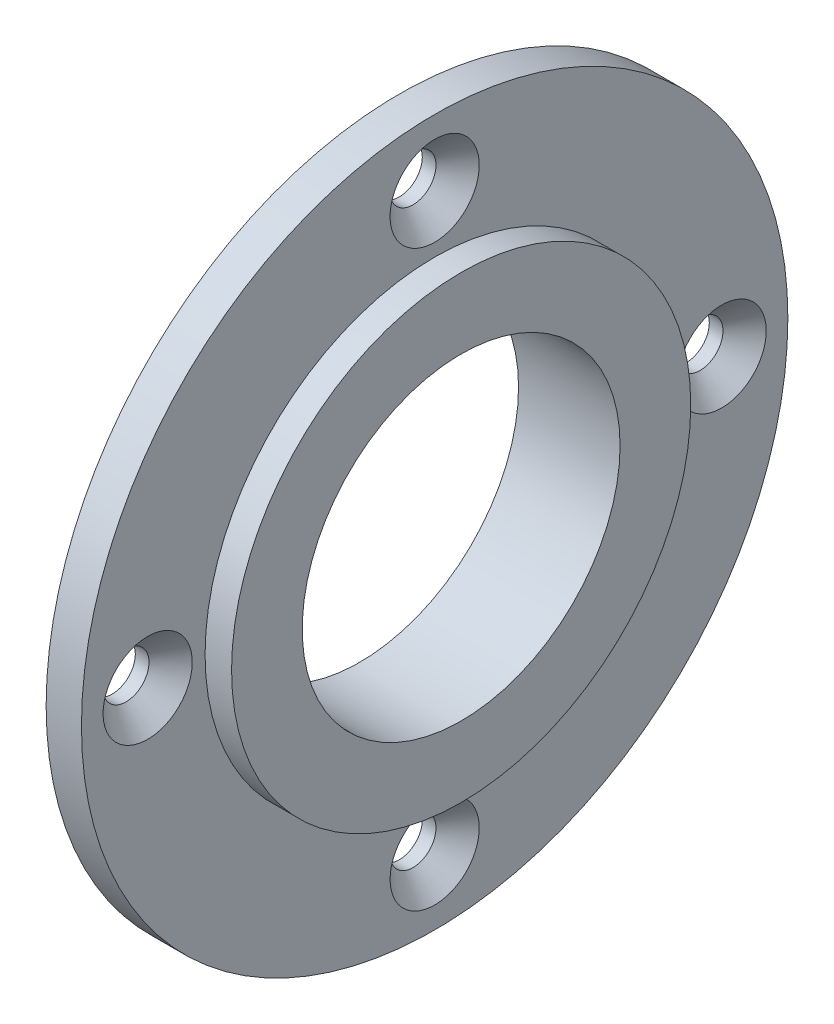
SolidWorks part; units mm, degrees
ref_plane "Front Plane" through (0, 0, 0) normal (0, 0, 1) x (1, 0, 0)
ref_plane "Top Plane" through (0, 0, 0) normal (0, 1, 0) x (1, 0, 0)
ref_plane "Right Plane" through (0, 0, 0) normal (1, 0, 0) x (0, 0, -1)
sketch "Sketch2" plane through (0, 0, 0) normal (0, 0, 1) x (1, 0, 0)
  line L0 (-174.9056, 26) -> (-177.9056, 26)
  line L1 (-177.9056, 26) -> (-177.9056, 40)
  line L2 (-177.9056, 40) -> (-181.9056, 40)
  line L3 (-181.9056, 40) -> (-181.9056, 21)
  line L4 (-186.4056, 18) -> (-174.9056, 18)
  line L5 (-174.9056, 18) -> (-174.9056, 26)
  line L6 (0, 0) -> (-61.0884, 0) construction
  line L7 (-182.4056, 18.3985) -> (-182.4056, 31.2775) construction
  line L8 (-181.9056, 21) -> (-186.4056, 21)
  line L9 (-186.4056, 21) -> (-186.4056, 18)
  line L14 (-198.4056, -21) -> (-198.4056, 21) construction
  dimension "D1" = 4
  dimension "D2" = 42
  dimension "D3" = 36
  dimension "D5" = 3
  dimension "D6" = 80
  dimension "D8" = 12
  dimension "D4" = 0.5
  dimension "D7" = 52
revolve "Revolve1" add sketch "Sketch2" angle 360 about L6
sketch "Sketch3" plane through (-177.9056, 0, 0) normal (1, 0, 0) x (0, 0, -1)
  circle A0 centre (0, 0) radius 32.5 construction
  circle A1 centre (0, 32.5) radius 3.3774
  dimension "D1" = 65
hole_wizard "CSK for M5 Countersunk Flat Head Screw1" positions "Sketch4" profile "Sketch5" countersink size "M5" standard "ISO" end condition through all
sketch "Sketch4" plane through (-177.9056, 0, 0) normal (1, 0, 0) x (0, 0, -1)
  point P0 (0, 32.5)
sketch "Sketch5" plane through (-177.9056, 32.5, 0) normal (0, 1, 0) x (0, 0, -1)
  line L0 (0, 0) -> (0, 8.5)
  line L1 (0, 8.5) -> (2.6, 8.5)
  line L2 (2.6, 8.5) -> (2.6, 2.45)
  line L3 (2.6, 2.45) -> (5.05, 0)
  line L5 (5.05, 0) -> (0, 0)
  line L6 (-2.6, 2.45) -> (-5.05, 0) construction
  line L11 (0, -6.35) -> (0, 107.95) construction
  dimension "Thru Hole Dia." = 5.2
  dimension "Thru Hole Depth" = 8.5
  dimension "Near C'Sink Dia." = 10.1
  dimension "Near C'Sink Angle" = 90
pattern_circular "CirPattern1" count 4 over 360 about axis through (0, 0, 0) along (1, 0, 0) of "CSK for M5 Countersunk Flat Head Screw1"
equation "\"l-x_vis_flasque_rouleau\"=4"
equation "\"D1@Sketch2\"= \"l-x_vis_flasque_rouleau\""
equation "\"d_ext_rouleau\"= 90"
equation "\"epaisseur_rouleau\"=80"
equation "\"alesage-rouleau\"= 52"
equation "\"jeu_dent_rouleau\"= 2"
equation "\"profondeur_dent_rouleau\"=4"
equation "\"n_dent_roueau\"= 15"
equation "\"B_roulement_rouleau\"= 12"
equation "\"F_anneau_alesage_rouleau\"=1.85"
equation "\"G_anneau_alesage_rouleau\"=47.5"
equation "\"K_anneau_alesage_rouleau\"=3.75"
equation "\"d_vis_flasque_rouleau\"=5"
equation "\"D2@Sketch2\" = \"d_ext_roulement_rouleau\""
equation "\"D3@Sketch2\"= \"d_ext_roulement_rouleau\" - 6"
equation "\"D8@Sketch2\"=\"B_roulement_rouleau\""
equation "\"g_anneau_arbre_rouleau\"=19"
equation "\"f_anneau_arbre_rouleau\"=1.3"
equation "\"k_anneau_arbre_rouleau\"=1.5"
equation "\"h_matrice\"= 18"
equation "\"d_matrice\"= 220"
equation "\"d_granulat\"= 8"
equation "\"zone_vide_matrice\" = 48"
equation "\"d_alesage_matrice\"=20"
equation "\"a_clavette_alesage_matrice\"=6"
equation "\"entrax_vis_rouleau\"=65"
equation "\"d_ext_roulement_rouleau\"= 42"
equation "\"d_int_roulement_rouleau\"= 20"
equation "\"D1@Sketch3\"=\"entrax_vis_rouleau\""
equation "\"D6@Sketch2\"=\"d_ext_rouleau\"-10"
equation "\"D7@Sketch2\"=\"alesage-rouleau\""
